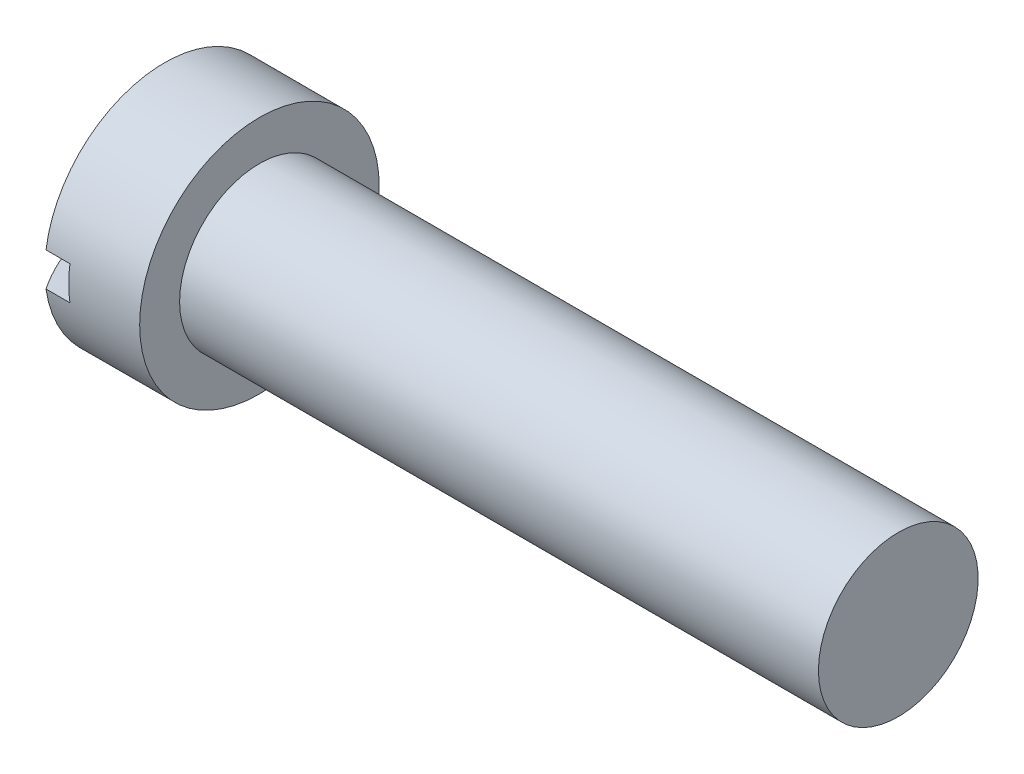
SolidWorks part; units mm, degrees
ref_plane "Plane1" through (0, 0, 0) normal (0, 0, 1) x (1, 0, 0)
ref_plane "Plane2" through (0, 0, 0) normal (0, 1, 0) x (1, 0, 0)
ref_plane "Plane3" through (0, 0, 0) normal (1, 0, 0) x (0, 0, -1)
sketch "BodySke" plane through (0, 0, 0) normal (0, 0, 1) x (1, 0, 0)
  line L0 (10.4648, 6.35) -> (10.4648, 9.525)
  line L1 (10.4648, 9.525) -> (2.921, 9.525)
  line L2 (-25.4, 0) -> (127, 0) construction
  line L3 (61.2648, 0) -> (0, 0)
  line L4 (10.4648, 6.35) -> (61.2648, 6.35)
  line L5 (61.2648, 6.35) -> (61.2648, 0)
  line L6 (10.4648, -9.525) -> (2.921, -9.525) construction
  line L7 (10.4648, -6.35) -> (61.2648, -6.35) construction
  line L8 (11.7348, 1.2192) -> (11.7348, -0.4698) construction
  line L9 (10.4648, 1.2192) -> (10.4648, -0.4698) construction
  arc A0 (0, 0) -> (2.921, 9.525) centre (16.9904, 0) cw
  dimension "Diameter" = 12.7
  dimension "Head_dia" = 19.05
  dimension "Head_ht" = 10.4648
  dimension "Length" = 50.8
  dimension "Head_side_ht" = 7.5438
  dimension "Thread_nom" = 50.8
  dimension "Advance" = 1.27
revolve "Base-Revolve" add sketch "BodySke" angle 360 about L2
cosmetic thread "ThreadCosmetic" [suppressed] parameters "Thread_length"=49.53, "Thread_minor"=11.1887
sketch "Sketch2" plane through (0, 0, 0) normal (1, 0, 0) x (0, 0, -1)
  line L0 (-9.525, -1.3462) -> (-9.525, 1.3462)
  line L1 (-9.525, 1.3462) -> (9.525, 1.3462)
  line L2 (9.525, 1.3462) -> (9.525, -1.3462)
  line L3 (9.525, -1.3462) -> (-9.525, -1.3462)
  dimension "D1" = 19.05
  dimension "D2" = 9.525
  dimension "D3" = 1.3462
  dimension "Slot_width" = 2.6924
extrude "Slot" cut sketch "Sketch2" along normal blind 4.826
sketch "Sketch3" plane through (0, 0, 0) normal (1, 0, 0) x (0, 0, -1)
  line L0 (1.1557, -7.1374) -> (-1.1557, -7.1374)
  line L1 (1.1557, -7.1374) -> (1.1557, 7.1374)
  line L2 (-1.1557, 7.1374) -> (1.1557, 7.1374)
  line L3 (-1.1557, 7.1374) -> (-1.1557, -7.1374)
  dimension "Cross_width" = 2.3114
  dimension "D1" = 1.1557
  dimension "Cross_dia" = 14.2748
  dimension "D2" = 7.1374
ref_plane "Plane4" through (8.6106, 0, 0) normal (1, 0, 0) x (0, 0, -1)
sketch "Sketch4" plane through (8.6106, 0, 0) normal (1, 0, 0) x (0, 0, -1)
  line L0 (0.5778, -0.5778) -> (-0.5778, -0.5779)
  line L1 (0.5778, -0.5778) -> (0.5779, 0.5778)
  line L2 (-0.5778, 0.5778) -> (0.5779, 0.5778)
  line L3 (-0.5778, 0.5778) -> (-0.5778, -0.5779)
  dimension "D1" = 1.1557
  dimension "D2" = 0.5778
  dimension "D3" = 1.1557
  dimension "D4" = 0.5778
loft "Cross" [suppressed] cut profiles "Sketch3", "Sketch4"
pattern_circular "CirPattern1" [suppressed] count 2 every 90 about axis through (-25.4, 0, 0) along (1, 0, 0)
sketch "Sketch5" plane through (0, 0, 0) normal (0, 1, 0) x (1, 0, 0)
  line L4 (-25.4, 0) -> (127, 0) construction
  line L5 (10.4648, -6.312) -> (10.4648, 6.3337) construction
  circle A0 centre (7.2709, 0) radius 0.889
  dimension "Drilled_hole_dia" = 1.778
  dimension "D1" = 10.4648
  dimension "Drilled_hole_loc" = 3.1939
extrude "Hole" [suppressed] cut sketch "Sketch5" against normal through all and the other way through all
sketch "ThdSchSke" plane through (0, 0, 0) normal (0, 0, 1) x (1, 0, 0)
  line L0 (11.7348, -5.5943) -> (11.2057, -6.35)
  line L1 (11.7348, -5.5943) -> (12.2639, -6.35)
  line L2 (12.2639, -6.35) -> (12.2639, -7.9375)
  line L3 (-3.175, 0) -> (5.1513, 0) construction
  line L5 (12.2639, -7.9375) -> (11.2057, -7.9375)
  line L6 (11.2057, -7.9375) -> (11.2057, -6.35)
  dimension "Diameter" = 12.7
  dimension "SideAngle" = 55
  dimension "VeeAngle" = 70
  dimension "Thread_minor" = 11.1887
  dimension "Overcut" = 15.875
  dimension "Start" = 11.7348
revolve "ThreadSchematic" [suppressed] cut sketch "ThdSchSke" angle 360 about L3
pattern_linear "ThdSchPat" [suppressed]
equation "\"D1@Sketch3\" = \"Cross_width@Sketch3\" / 2"
equation "\"D2@Sketch3\" = \"Cross_dia@Sketch3\" / 2"
equation "\"D1@Sketch4\" = \"Cross_width@Sketch3\"*.5"
equation "\"D2@Sketch4\" = \"D1@Sketch4\" / 2"
equation "\"D3@Sketch4\" = \"D1@Sketch4\""
equation "\"D4@Sketch4\" = \"D2@Sketch4\""
equation "\"D1@Sketch2\" = \"Head_dia@BodySke\""
equation "\"D2@Sketch2\" = \"D1@Sketch2\" / 2"
equation "\"D3@Sketch2\" = \"Slot_width@Sketch2\" / 2"
equation "\"D1@Sketch5\" = \"Head_ht@BodySke\""
equation "\"Thread_length@ThreadCosmetic\" = ((sgn( (\"Length@BodySke\" - \"Advance@BodySke\" ) - \"Thread_nom@BodySke\" )-1)*( (\"Length@BodySke\" - \"Advance@BodySke\" ) - \"Thread_nom@BodySke\" ))/-2+ \"Thread_nom@BodySke\""
equation "\"Thread_minor@ThdSchSke\" = \"Thread_minor@ThreadCosmetic\""
equation "\"Diameter@ThdSchSke\" = \"Diameter@BodySke\""
equation "\"Overcut@ThdSchSke\" = \"Diameter@BodySke\" * 1.25"
equation "\"Start@ThdSchSke\" = \"Head_ht@BodySke\" + \"Length@BodySke\" - \"Thread_length@ThreadCosmetic\"  '---Non-countersunk---"
equation "\"Num_threads@ThdSchPat\" = int( \"Thread_length@ThreadCosmetic\" / \"Advance@BodySke\" + 0.999 )  + 1"
equation "\"Advance@ThdSchPat\" = \"Thread_length@ThreadCosmetic\" /  (\"Num_threads@ThdSchPat\" - 1) 'relax it"
